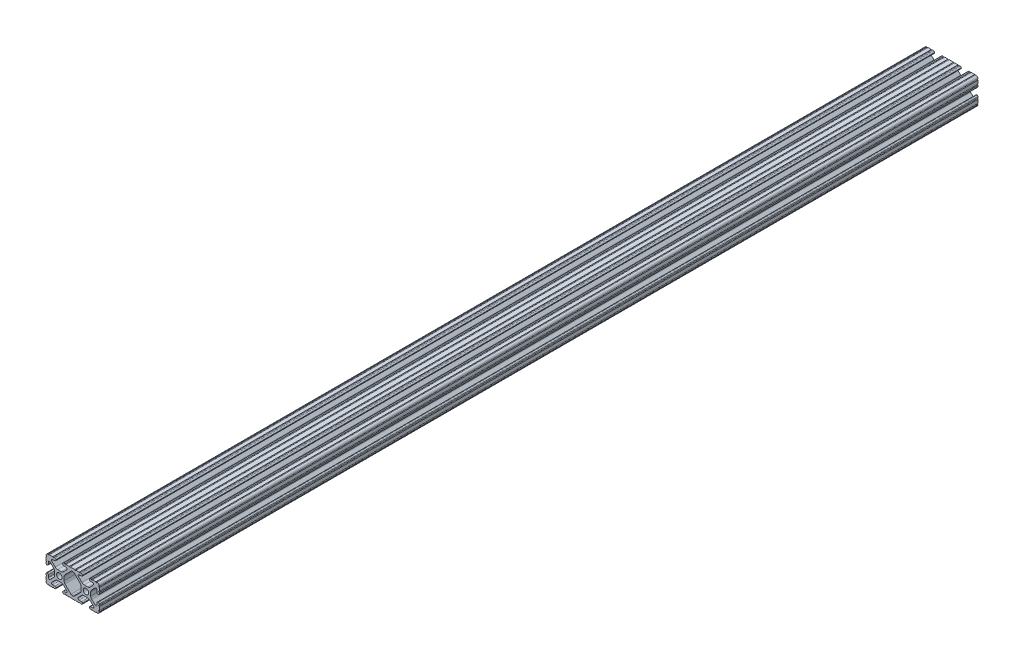
SolidWorks part; units mm, degrees
ref_plane "Front Plane" through (0, 0, 0) normal (0, 0, 1) x (1, 0, 0)
ref_plane "Top Plane" through (0, 0, 0) normal (0, 1, 0) x (1, 0, 0)
ref_plane "Right Plane" through (0, 0, 0) normal (1, 0, 0) x (0, 0, -1)
sketch "Sketch1" plane through (0, 0, 0) normal (0, 0, 1) x (1, 0, 0)
  line L0 (-7.2595, -3.8694) -> (-1.5457, -9.5728)
  line L1 (-8.1915, 1.6223) -> (-8.1915, -1.6223)
  line L2 (-1.504, 9.5765) -> (-7.252, 3.8768)
  line L3 (0.5515, 10.033) -> (-0.3952, 10.033)
  line L4 (7.2829, 3.8459) -> (1.6756, 9.5611)
  line L5 (8.1915, -1.6223) -> (8.1915, 1.6223)
  line L6 (1.5457, -9.5728) -> (7.2595, -3.8694)
  line L7 (-0.4332, -10.033) -> (0.4332, -10.033)
  line L8 (18.0171, 12.7) -> (16.9875, 12.7)
  line L9 (15.9385, 11.651) -> (15.9385, 11.5392)
  line L10 (16.9875, 10.4902) -> (19.1164, 10.4902)
  line L11 (19.8441, 8.7652) -> (16.619, 5.4551)
  line L12 (14.3449, 4.4958) -> (11.0833, 4.4958)
  line L13 (8.817, 5.4472) -> (5.5642, 8.7627)
  line L14 (6.2894, 10.4902) -> (8.4125, 10.4902)
  line L15 (9.4615, 11.5392) -> (9.4615, 11.651)
  line L16 (8.4125, 12.7) -> (7.3829, 12.7)
  line L17 (6.3669, 12.7) -> (3.1496, 12.7)
  line L18 (2.1336, 12.7) -> (-2.1336, 12.7)
  line L19 (-3.1496, 12.7) -> (-6.3669, 12.7)
  line L20 (-7.3829, 12.7) -> (-8.4125, 12.7)
  line L21 (-9.4615, 11.651) -> (-9.4615, 11.5392)
  line L22 (-8.4125, 10.4902) -> (-6.2836, 10.4902)
  line L23 (-5.5326, 8.6661) -> (-8.81, 5.4163)
  line L24 (-11.0455, 4.4958) -> (-14.3545, 4.4958)
  line L25 (-16.59, 5.4163) -> (-19.8674, 8.6661)
  line L26 (-19.1164, 10.4902) -> (-16.9875, 10.4902)
  line L27 (-15.9385, 11.5392) -> (-15.9385, 11.651)
  line L28 (-16.9875, 12.7) -> (-18.0171, 12.7)
  line L29 (-19.0331, 12.7) -> (-22.2504, 12.7)
  line L30 (-25.4, 9.5504) -> (-25.4, 6.3331)
  line L31 (-25.4, 5.3171) -> (-25.4, 4.2375)
  line L32 (-24.401, 3.2385) -> (-24.2392, 3.2385)
  line L33 (-23.1902, 4.2875) -> (-23.1902, 6.3347)
  line L34 (-21.434, 7.0665) -> (-18.148, 3.8082)
  line L35 (-17.2085, 1.5536) -> (-17.2085, -1.6952)
  line L36 (-18.1405, -3.9423) -> (-21.4316, -7.2274)
  line L37 (-23.1902, -6.498) -> (-23.1902, -4.2875)
  line L38 (-24.2392, -3.2385) -> (-24.351, -3.2385)
  line L39 (-25.4, -4.2875) -> (-25.4, -5.3171)
  line L40 (-25.4, -6.3331) -> (-25.4, -9.5504)
  line L41 (-22.2504, -12.7) -> (-19.0331, -12.7)
  line L42 (-18.0171, -12.7) -> (-16.9875, -12.7)
  line L43 (-15.9384, -11.651) -> (-15.9384, -11.5392)
  line L44 (-16.9875, -10.4902) -> (-19.1164, -10.4902)
  line L45 (-19.8341, -8.7551) -> (-16.4966, -5.4237)
  line L46 (-14.2536, -4.4958) -> (-11.1464, -4.4958)
  line L47 (-8.9034, -5.4237) -> (-5.5659, -8.7551)
  line L48 (-6.2836, -10.4902) -> (-8.4125, -10.4902)
  line L49 (-9.4616, -11.5392) -> (-9.4616, -11.651)
  line L50 (-8.4125, -12.7) -> (-7.3829, -12.7)
  line L51 (-6.3669, -12.7) -> (-3.1496, -12.7)
  line L52 (-2.1336, -12.7) -> (2.1336, -12.7)
  line L53 (3.1496, -12.7) -> (6.3669, -12.7)
  line L54 (7.3829, -12.7) -> (8.4125, -12.7)
  line L55 (9.4616, -11.651) -> (9.4616, -11.5392)
  line L56 (8.4125, -10.4902) -> (6.2894, -10.4902)
  line L57 (5.4807, -8.5353) -> (8.5979, -5.4237)
  line L58 (10.8409, -4.4958) -> (14.1026, -4.4958)
  line L59 (16.1879, -5.2766) -> (19.8682, -8.4822)
  line L60 (19.1164, -10.4902) -> (16.9875, -10.4902)
  line L61 (15.9384, -11.5392) -> (15.9384, -11.651)
  line L62 (16.9875, -12.7) -> (18.0171, -12.7)
  line L63 (19.0331, -12.7) -> (22.2504, -12.7)
  line L64 (25.4, -9.5504) -> (25.4, -6.3331)
  line L65 (25.4, -5.3171) -> (25.4, -4.2375)
  line L66 (24.401, -3.2385) -> (24.1892, -3.2385)
  line L67 (23.1902, -4.2375) -> (23.1902, -6.1559)
  line L68 (21.584, -6.8869) -> (18.2982, -4.025)
  line L69 (17.2085, -1.6308) -> (17.2085, 1.6308)
  line L70 (18.1094, 3.8465) -> (21.5263, 7.3534)
  line L71 (23.1902, 6.6769) -> (23.1902, 4.2375)
  line L72 (24.1892, 3.2385) -> (24.401, 3.2385)
  line L73 (25.4, 4.2375) -> (25.4, 5.3171)
  line L74 (25.4, 6.3332) -> (25.4, 9.5504)
  line L75 (22.2504, 12.7) -> (19.0331, 12.7)
  circle A0 centre (-12.7, 0) radius 2.6035
  circle A1 centre (12.7, 0) radius 2.6035
  arc A2 (-1.5457, -9.5728) -> (-0.4332, -10.033) centre (-0.4332, -8.4582) ccw
  arc A3 (-8.1915, -1.6223) -> (-7.2595, -3.8694) centre (-5.0165, -1.6223) ccw
  arc A4 (-7.252, 3.8768) -> (-8.1915, 1.6223) centre (-5.0165, 1.6223) ccw
  arc A5 (-0.3952, 10.033) -> (-1.504, 9.5765) centre (-0.3952, 8.4582) ccw
  arc A6 (1.6756, 9.5611) -> (0.5515, 10.033) centre (0.5515, 8.4582) ccw
  arc A7 (8.1915, 1.6223) -> (7.2829, 3.8459) centre (5.0165, 1.6223) ccw
  arc A8 (7.2595, -3.8694) -> (8.1915, -1.6223) centre (5.0165, -1.6223) ccw
  arc A9 (0.4332, -10.033) -> (1.5457, -9.5728) centre (0.4332, -8.4582) ccw
  arc A10 (18.0171, 12.7) -> (19.0331, 12.7) centre (18.5251, 12.7) ccw
  arc A11 (16.9875, 12.7) -> (15.9385, 11.651) centre (16.9875, 11.651) ccw
  arc A12 (15.9385, 11.5392) -> (16.9875, 10.4902) centre (16.9875, 11.5392) ccw
  arc A13 (19.8441, 8.7652) -> (19.1164, 10.4902) centre (19.1164, 9.4742) ccw
  arc A14 (14.3449, 4.4958) -> (16.619, 5.4551) centre (14.3449, 7.6708) ccw
  arc A15 (8.817, 5.4472) -> (11.0833, 4.4958) centre (11.0833, 7.6708) ccw
  arc A16 (6.2894, 10.4902) -> (5.5642, 8.7627) centre (6.2894, 9.4742) ccw
  arc A17 (8.4125, 10.4902) -> (9.4615, 11.5392) centre (8.4125, 11.5392) ccw
  arc A18 (9.4615, 11.651) -> (8.4125, 12.7) centre (8.4125, 11.651) ccw
  arc A19 (6.3669, 12.7) -> (7.3829, 12.7) centre (6.8749, 12.7) ccw
  arc A20 (2.1336, 12.7) -> (3.1496, 12.7) centre (2.6416, 12.7) ccw
  arc A21 (-3.1496, 12.7) -> (-2.1336, 12.7) centre (-2.6416, 12.7) ccw
  arc A22 (-7.3829, 12.7) -> (-6.3669, 12.7) centre (-6.8749, 12.7) ccw
  arc A23 (-8.4125, 12.7) -> (-9.4615, 11.651) centre (-8.4125, 11.651) ccw
  arc A24 (-9.4615, 11.5392) -> (-8.4125, 10.4902) centre (-8.4125, 11.5392) ccw
  arc A25 (-5.5326, 8.6661) -> (-6.2836, 10.4902) centre (-6.2836, 9.4235) ccw
  arc A26 (-11.0455, 4.4958) -> (-8.81, 5.4163) centre (-11.0455, 7.6708) ccw
  arc A27 (-16.59, 5.4163) -> (-14.3545, 4.4958) centre (-14.3545, 7.6708) ccw
  arc A28 (-19.1164, 10.4902) -> (-19.8674, 8.6661) centre (-19.1164, 9.4235) ccw
  arc A29 (-16.9875, 10.4902) -> (-15.9385, 11.5392) centre (-16.9875, 11.5392) ccw
  arc A30 (-15.9385, 11.651) -> (-16.9875, 12.7) centre (-16.9875, 11.651) ccw
  arc A31 (-19.0331, 12.7) -> (-18.0171, 12.7) centre (-18.5251, 12.7) ccw
  arc A32 (-23.2664, 12.6998) -> (-22.2504, 12.7) centre (-22.7584, 12.7) ccw
  arc A33 (-23.2664, 12.6998) -> (-25.3998, 10.5664) centre (-23.2918, 10.5918) ccw
  arc A34 (-25.4, 9.5504) -> (-25.3998, 10.5664) centre (-25.4, 10.0584) ccw
  arc A35 (-25.4, 5.3171) -> (-25.4, 6.3331) centre (-25.4, 5.8251) ccw
  arc A36 (-25.4, 4.2375) -> (-24.401, 3.2385) centre (-24.401, 4.2375) ccw
  arc A37 (-24.2392, 3.2385) -> (-23.1902, 4.2875) centre (-24.2392, 4.2875) ccw
  arc A38 (-21.434, 7.0665) -> (-23.1902, 6.3347) centre (-22.1596, 6.3347) ccw
  arc A39 (-17.2085, 1.5536) -> (-18.148, 3.8082) centre (-20.3835, 1.5536) ccw
  arc A40 (-18.1405, -3.9423) -> (-17.2085, -1.6952) centre (-20.3835, -1.6952) ccw
  arc A41 (-23.1902, -6.498) -> (-21.4316, -7.2274) centre (-22.1596, -6.498) ccw
  arc A42 (-23.1902, -4.2875) -> (-24.2392, -3.2385) centre (-24.2392, -4.2875) ccw
  arc A43 (-24.351, -3.2385) -> (-25.4, -4.2875) centre (-24.351, -4.2875) ccw
  arc A44 (-25.4, -6.3331) -> (-25.4, -5.3171) centre (-25.4, -5.8251) ccw
  arc A45 (-25.3998, -10.5664) -> (-25.4, -9.5504) centre (-25.4, -10.0584) ccw
  arc A46 (-25.3998, -10.5664) -> (-23.2664, -12.6998) centre (-23.2918, -10.5918) ccw
  arc A47 (-22.2504, -12.7) -> (-23.2664, -12.6998) centre (-22.7584, -12.7) ccw
  arc A48 (-18.0171, -12.7) -> (-19.0331, -12.7) centre (-18.5251, -12.7) ccw
  arc A49 (-16.9875, -12.7) -> (-15.9384, -11.651) centre (-16.9875, -11.651) ccw
  arc A50 (-15.9384, -11.5392) -> (-16.9875, -10.4902) centre (-16.9875, -11.5392) ccw
  arc A51 (-19.8341, -8.7551) -> (-19.1164, -10.4902) centre (-19.1164, -9.4742) ccw
  arc A52 (-14.2536, -4.4958) -> (-16.4966, -5.4237) centre (-14.2536, -7.6708) ccw
  arc A53 (-8.9034, -5.4237) -> (-11.1464, -4.4958) centre (-11.1464, -7.6708) ccw
  arc A54 (-6.2836, -10.4902) -> (-5.5659, -8.7551) centre (-6.2836, -9.4742) ccw
  arc A55 (-8.4125, -10.4902) -> (-9.4616, -11.5392) centre (-8.4125, -11.5392) ccw
  arc A56 (-9.4616, -11.651) -> (-8.4125, -12.7) centre (-8.4125, -11.651) ccw
  arc A57 (-6.3669, -12.7) -> (-7.3829, -12.7) centre (-6.8749, -12.7) ccw
  arc A58 (-2.1336, -12.7) -> (-3.1496, -12.7) centre (-2.6416, -12.7) ccw
  arc A59 (3.1496, -12.7) -> (2.1336, -12.7) centre (2.6416, -12.7) ccw
  arc A60 (7.3829, -12.7) -> (6.3669, -12.7) centre (6.8749, -12.7) ccw
  arc A61 (8.4125, -12.7) -> (9.4616, -11.651) centre (8.4125, -11.651) ccw
  arc A62 (9.4616, -11.5392) -> (8.4125, -10.4902) centre (8.4125, -11.5392) ccw
  arc A63 (5.4807, -8.5353) -> (6.2894, -10.4902) centre (6.2894, -9.3455) ccw
  arc A64 (10.8409, -4.4958) -> (8.5979, -5.4237) centre (10.8409, -7.6708) ccw
  arc A65 (16.1879, -5.2766) -> (14.1026, -4.4958) centre (14.1026, -7.6708) ccw
  arc A66 (19.1164, -10.4902) -> (19.8682, -8.4822) centre (19.1164, -9.3455) ccw
  arc A67 (16.9875, -10.4902) -> (15.9384, -11.5392) centre (16.9875, -11.5392) ccw
  arc A68 (15.9384, -11.651) -> (16.9875, -12.7) centre (16.9875, -11.651) ccw
  arc A69 (19.0331, -12.7) -> (18.0171, -12.7) centre (18.5251, -12.7) ccw
  arc A70 (23.2664, -12.6998) -> (22.2504, -12.7) centre (22.7584, -12.7) ccw
  arc A71 (23.2664, -12.6998) -> (25.3998, -10.5664) centre (23.2918, -10.5918) ccw
  arc A72 (25.4, -9.5504) -> (25.3998, -10.5664) centre (25.4, -10.0584) ccw
  arc A73 (25.4, -5.3171) -> (25.4, -6.3331) centre (25.4, -5.8251) ccw
  arc A74 (25.4, -4.2375) -> (24.401, -3.2385) centre (24.401, -4.2375) ccw
  arc A75 (24.1892, -3.2385) -> (23.1902, -4.2375) centre (24.1892, -4.2375) ccw
  arc A76 (21.584, -6.8869) -> (23.1902, -6.1559) centre (22.2207, -6.1559) ccw
  arc A77 (17.2085, -1.6308) -> (18.2982, -4.025) centre (20.3835, -1.6308) ccw
  arc A78 (18.1094, 3.8465) -> (17.2085, 1.6308) centre (20.3835, 1.6308) ccw
  arc A79 (23.1902, 6.6769) -> (21.5263, 7.3534) centre (22.2207, 6.6769) ccw
  arc A80 (23.1902, 4.2375) -> (24.1892, 3.2385) centre (24.1892, 4.2375) ccw
  arc A81 (24.401, 3.2385) -> (25.4, 4.2375) centre (24.401, 4.2375) ccw
  arc A82 (25.4, 6.3332) -> (25.4, 5.3171) centre (25.4, 5.8251) ccw
  arc A83 (25.3998, 10.5664) -> (25.4, 9.5504) centre (25.4, 10.0584) ccw
  arc A84 (25.3998, 10.5664) -> (23.2664, 12.6998) centre (23.2918, 10.5918) ccw
  arc A85 (22.2504, 12.7) -> (23.2664, 12.6998) centre (22.7584, 12.7) ccw
  point P248 (0, 10.033)
extrude "Boss-Extrude1" add sketch "Sketch1" along normal mid plane 838.2
